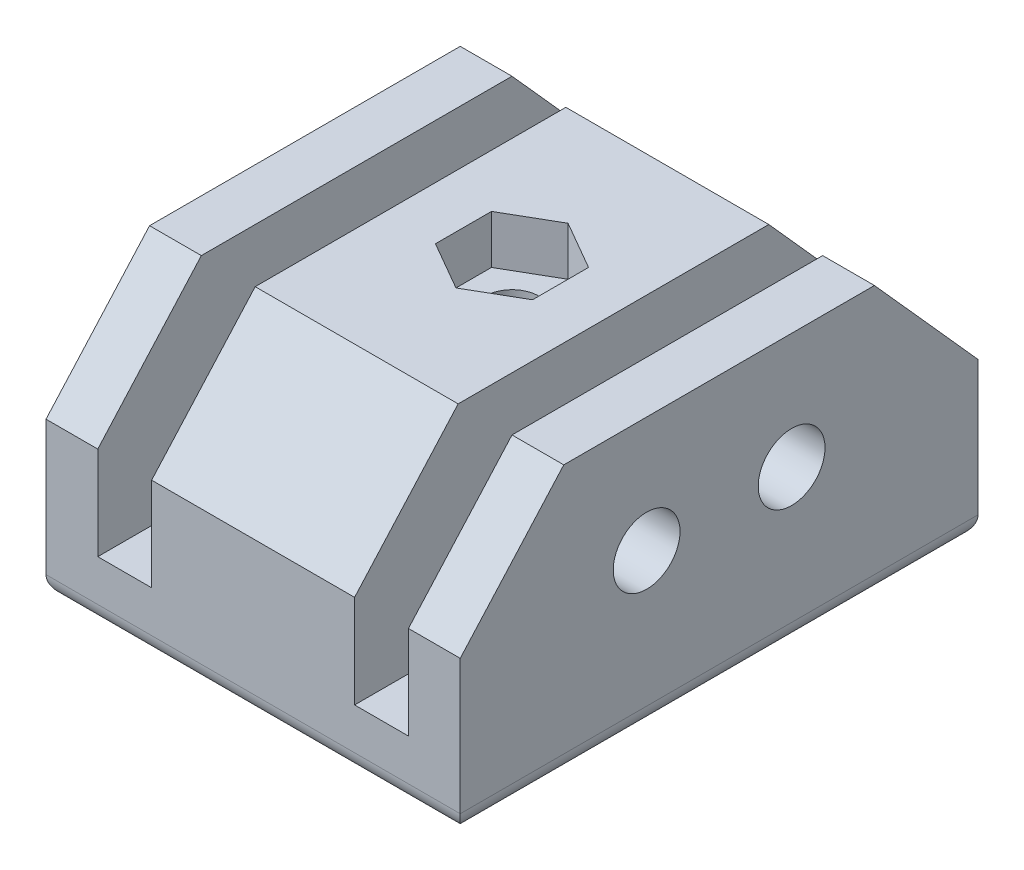
SolidWorks part; units mm, degrees
ref_plane "Front Plane" through (0, 0, 0) normal (0, 0, 1) x (1, 0, 0)
ref_plane "Top Plane" through (0, 0, 0) normal (0, 1, 0) x (1, 0, 0)
ref_plane "Right Plane" through (0, 0, 0) normal (1, 0, 0) x (0, 0, -1)
sketch "Sketch1" plane through (0, 0, 0) normal (1, 0, 0) x (0, 0, -1)
  line L1 (0, 0) -> (63.5, 0)
  line L2 (0, 0) -> (0, 6.35)
  line L3 (0, 6.35) -> (63.5, 6.35)
  line L4 (63.5, 0) -> (63.5, 6.35)
  dimension "D1" = 6.35
  dimension "D2" = 63.5
extrude "Boss-Extrude1" add sketch "Sketch1" against normal blind 50.8
sketch "Sketch2" plane through (0, 0, 0) normal (1, 0, 0) x (0, 0, -1)
  line L0 (0, 6.35) -> (0, 19.05)
  line L1 (0, 19.05) -> (12.7, 33.249)
  line L2 (12.7, 33.249) -> (50.8, 33.249)
  line L3 (50.8, 33.249) -> (63.5, 19.05)
  line L4 (63.5, 19.05) -> (63.5, 6.35)
  line L5 (63.5, 6.35) -> (0, 6.35)
  point P7 (31.75, 33.249)
  point P10 (31.75, 6.35)
  dimension "D1" = 38.1
  dimension "D2" = 12.7
  dimension "D3" = 12.7
  dimension "D4" = 19.05
  dimension "D5" = 19.05
extrude "Boss-Extrude2" add sketch "Sketch2" against normal blind 50.8
sketch "Sketch10" plane through (0, 0, -63.5) normal (0, 0, -1) x (-1, 0, 0)
  line L1 (50.8, 33.249) -> (0, 33.249) construction
  line L3 (6.35, 7.62) -> (6.35, 33.249)
  line L4 (6.35, 33.249) -> (12.954, 33.249)
  line L5 (12.954, 7.62) -> (12.954, 33.249)
  line L6 (6.35, 7.62) -> (12.954, 7.62)
  line L8 (50.8, 0) -> (0, 0) construction
  point P11 (12.954, 7.62)
  dimension "D1" = 7.62
  dimension "D2" = 6.604
  dimension "D3" = 6.35
extrude "Cut-Extrude1" cut sketch "Sketch10" against normal through all
pattern_linear "LPattern3" count 2 spacing 31.496 along (-1, 0, 0) of "Cut-Extrude1"
sketch "Sketch11" plane through (0, 0, 0) normal (1, 0, 0) x (0, 0, -1)
  circle A0 centre (22.86, 19.05) radius 4.0957
  circle A1 centre (22.86, 19.05) radius 7.9375 construction
  circle A2 centre (40.64, 19.05) radius 4.0958
  circle A3 centre (40.64, 19.05) radius 7.9375 construction
  dimension "D1" = 8.1915
  dimension "D3" = 15.875
  dimension "D4" = 8.1915
  dimension "D6" = 15.875
  dimension "D2" = 10.16
  dimension "D5" = 10.16
extrude "Cut-Extrude2" cut sketch "Sketch11" against normal through all
sketch "Sketch14" plane through (0, 33.249, 0) normal (0, 1, 0) x (1, 0, 0)
  line L3 (-37.846, 12.7) -> (-37.846, 50.8) construction
  point P0 (-25.4, 31.75)
  point P4 (-37.846, 31.75)
  dimension "D1" = 12.446
sketch "Sketch17" plane through (0, 40.0201, -44.7438) normal (0, 0.6667, -0.7454) x (-1, 0, 0)
  line L0 (12.954, -28.1343) -> (12.954, -9.0843) construction
  line L1 (37.846, -9.0843) -> (12.954, -9.0843) construction
  point P0 (25.4, -18.6093)
  point P1 (22.4146, -41.3668)
  point P4 (12.954, -18.6093)
  point P7 (25.4, -9.0843)
  point P8 (0, 0)
  point P9 (0, 0)
  point P10 (-64072.0164, 690029.433)
  point P11 (0, 0)
sketch "Sketch18" plane through (0, 8.4667, 9.466) normal (0, 0.6667, 0.7454) x (1, 0, 0)
  line L0 (-12.954, 33.249) -> (-12.954, 14.199) construction
  line L1 (-37.846, 33.249) -> (-12.954, 33.249) construction
  point P0 (-25.4, 23.724)
  point P1 (-25.4, 23.724)
  point P4 (-12.954, 23.724)
  point P7 (-25.4, 33.249)
ref_plane "Plane2" through (0, 33.02, 0) normal (0, -1, 0) x (-1, 0, 0)
sketch "Sketch19" plane through (0, 33.249, 0) normal (0, 1, 0) x (1, 0, 0)
  line L1 (-19.4489, 35.1859) -> (-25.4, 38.6217)
  line L2 (-25.4, 38.6217) -> (-31.3511, 35.1859)
  line L3 (-31.3511, 35.1859) -> (-31.3511, 28.3141)
  line L4 (-31.3511, 28.3141) -> (-25.4, 24.8783)
  line L5 (-25.4, 24.8783) -> (-19.4489, 28.3141)
  line L6 (-19.4489, 28.3141) -> (-19.4489, 35.1859)
  line L7 (-37.846, 12.7) -> (-12.954, 12.7) construction
  line L8 (-37.846, 12.7) -> (-37.846, 50.8) construction
  circle A0 centre (-25.4, 31.75) radius 5.9511 construction
  point P1 (-19.4489, 31.75)
  point P11 (-25.4, 12.7)
  point P14 (-37.846, 31.75)
  dimension "D1" = 11.9022
extrude "Cut-Extrude3" cut sketch "Sketch19" against normal blind 5.9531
pattern_linear "LPattern4" count 2 spacing 27.94 along (0, -1, 0) of "Cut-Extrude3"
sketch "Sketch20" plane through (0, 27.2959, 0) normal (0, 1, 0) x (1, 0, 0)
  line L0 (-19.4489, 28.3141) -> (-19.4489, 35.1859) construction
  line L1 (-37.846, 50.8) -> (-12.954, 50.8) construction
  circle A0 centre (-25.4, 31.75) radius 3.302
  point P4 (-19.4489, 31.75)
  point P8 (-25.4, 50.8)
  dimension "D1" = 6.604
extrude "Cut-Extrude4" cut sketch "Sketch20" against normal up to surface (21.9869 mm away) up to face at (-25.4, 5.309, -31.75)
fillet "Fillet1" radius 2.54 4 edges at (0, 0, -31.75) (-50.8, 0, -31.75) (-25.4, 0, 0) (-25.4, 0, -63.5)
